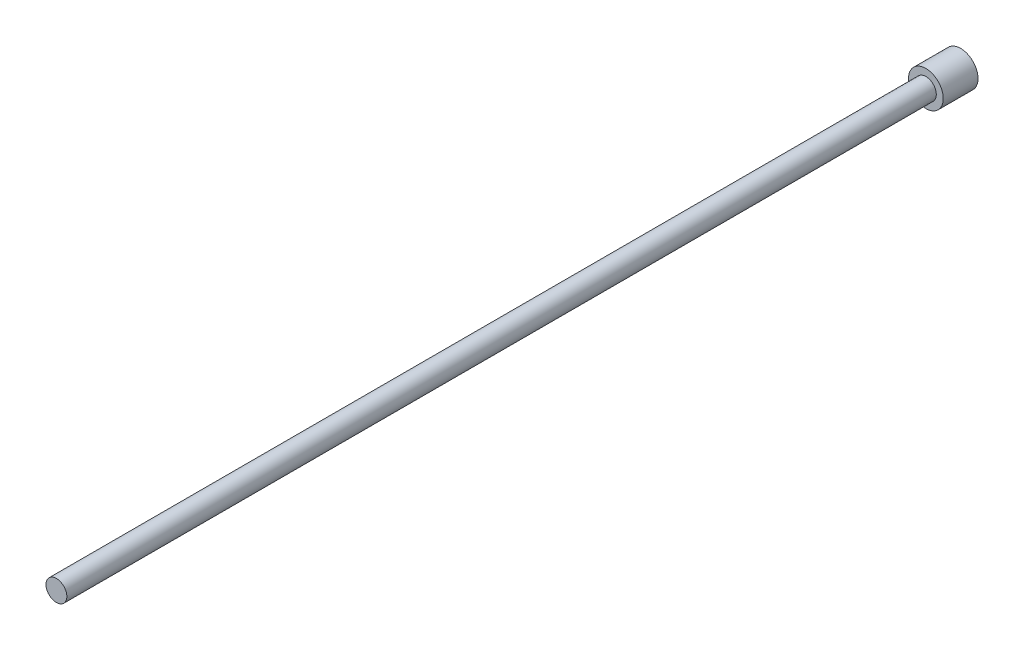
SolidWorks part; units mm, degrees
ref_plane "Alzado" through (0, 0, 0) normal (0, 0, 1) x (1, 0, 0)
ref_plane "Planta" through (0, 0, 0) normal (0, 1, 0) x (1, 0, 0)
ref_plane "Vista lateral" through (0, 0, 0) normal (1, 0, 0) x (0, 0, -1)
sketch "Croquis1" plane through (0, 0, 0) normal (0, 0, 1) x (1, 0, 0)
  circle A0 centre (0, 0) radius 0.6
  dimension "D1" = 1.2
extrude "Saliente-Extruir1" add sketch "Croquis1" along normal blind 50
sketch "Croquis2" plane through (0, 0, 0) normal (0, 0, -1) x (-1, 0, 0)
  circle A0 centre (0, 0) radius 1
  dimension "D1" = 2
extrude "Saliente-Extruir2" add sketch "Croquis2" along normal blind 2
